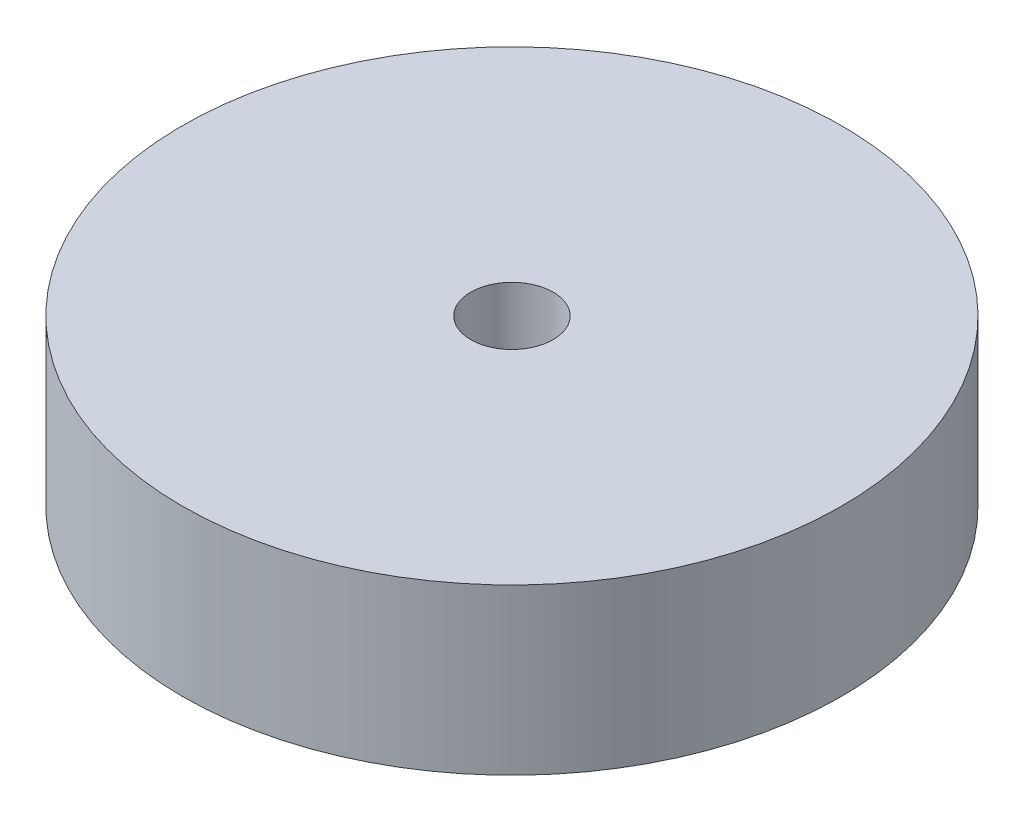
SolidWorks part; units mm, degrees
ref_plane "Front Plane" through (0, 0, 0) normal (0, 0, 1) x (1, 0, 0)
ref_plane "Top Plane" through (0, 0, 0) normal (0, 1, 0) x (1, 0, 0)
ref_plane "Right Plane" through (0, 0, 0) normal (1, 0, 0) x (0, 0, -1)
sketch "Sketch1" plane through (0, 0, 0) normal (0, 1, 0) x (1, 0, 0)
  circle A0 centre (0, 0) radius 3.175
  circle A1 centre (0, 0) radius 0.3969
  dimension "D1" = 0.7937
  dimension "D2" = 6.35
extrude "Boss-Extrude1" add sketch "Sketch1" along normal blind 1.5875
